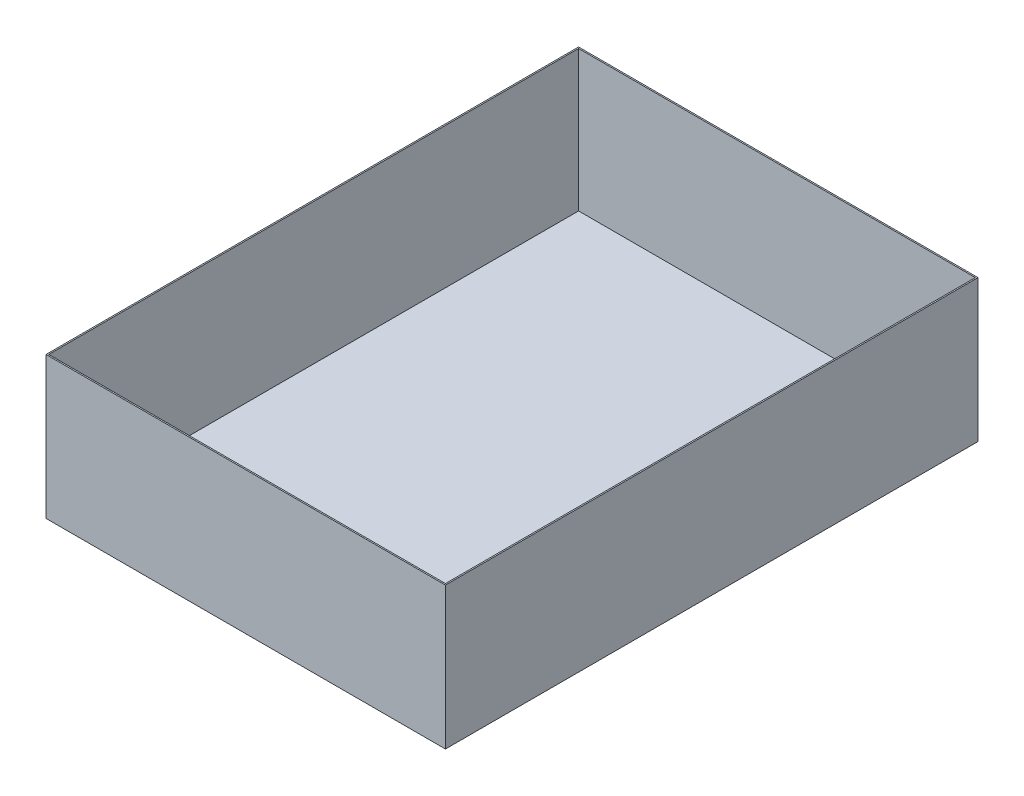
SolidWorks part; units mm, degrees
ref_plane "Front Plane" through (0, 0, 0) normal (0, 0, 1) x (1, 0, 0)
ref_plane "Top Plane" through (0, 0, 0) normal (0, 1, 0) x (1, 0, 0)
ref_plane "Right Plane" through (0, 0, 0) normal (1, 0, 0) x (0, 0, -1)
sketch "Sketch1" plane through (0, 0, 0) normal (0, 1, 0) x (1, 0, 0)
  line L1 (0, 0) -> (450, 0)
  line L2 (0, 0) -> (0, 600)
  line L3 (0, 600) -> (450, 600)
  line L4 (450, 0) -> (450, 600)
  dimension "D1" = 450
  dimension "D2" = 600
extrude "Boss-Extrude1" add sketch "Sketch1" along normal blind 160
sketch "Sketch2" plane through (0, 160, 0) normal (0, 1, 0) x (1, 0, 0)
  line L0 (1.5, 598.5) -> (1.5, 1.5)
  line L1 (1.5, 1.5) -> (448.5, 1.5)
  line L2 (448.5, 1.5) -> (448.5, 598.5)
  line L3 (448.5, 598.5) -> (1.5, 598.5)
  line L4 (0, 600) -> (0, 0)
  line L5 (0, 0) -> (450, 0)
  line L6 (450, 0) -> (450, 600)
  line L7 (450, 600) -> (0, 600)
  line L8 (0, 600) -> (0, 0)
  line L9 (0, 0) -> (450, 0)
  line L10 (450, 0) -> (450, 600)
  line L11 (450, 600) -> (0, 600)
  dimension "D1" = 0
  dimension "D2" = 1.5
extrude "Cut-Extrude1" cut sketch "Sketch2" against normal offset from surface (158.5 mm away) 1.5 contours L2 L3 L0 L1 up to face at (225, 0, -300)
